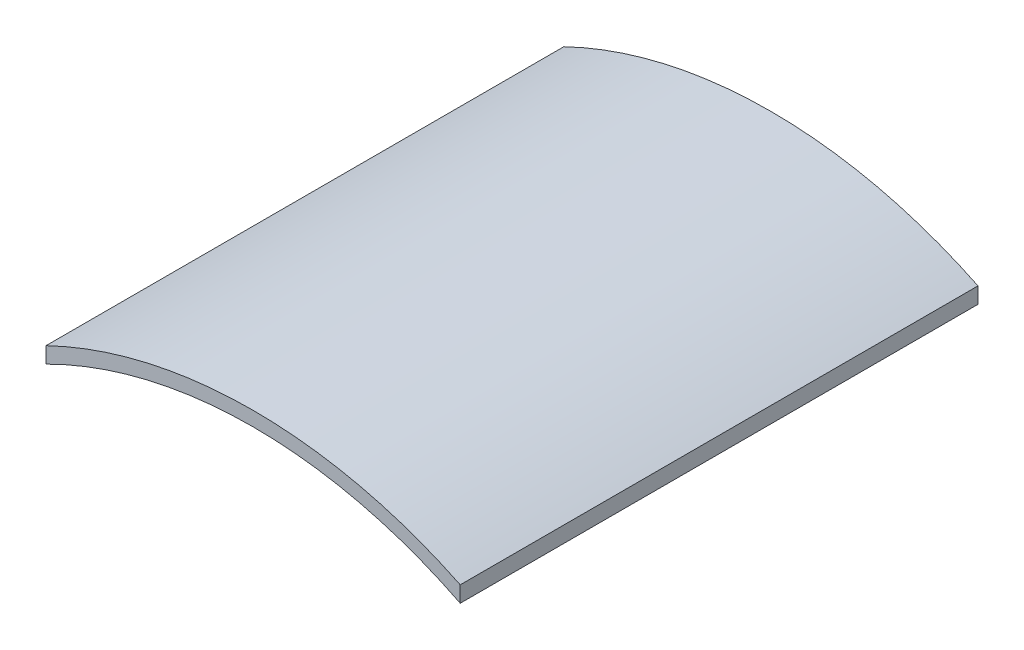
SolidWorks part; units mm, degrees
ref_plane "Front Plane" through (0, 0, 0) normal (0, 0, 1) x (1, 0, 0)
ref_plane "Top Plane" through (0, 0, 0) normal (0, 1, 0) x (1, 0, 0)
ref_plane "Right Plane" through (0, 0, 0) normal (1, 0, 0) x (0, 0, -1)
sketch "Sketch1" plane through (0, 0, 0) normal (0, 0, 1) x (1, 0, 0)
  line L4 (-24, 49.4874) -> (-24, 47.6338)
  line L5 (24, 49.4874) -> (24, 47.6338)
  arc A0 (-24, 49.4874) -> (24, 49.4874) centre (0, 0) cw
  arc A1 (-24, 47.6338) -> (24, 47.6338) centre (0, 0) cw
  point P9 (0, 53.3383)
  point P11 (-24, 48.5606)
  dimension "D1" = 1.8536
  dimension "D2" = 53.3383
  dimension "D4" = 48
extrude "Boss-Extrude1" add sketch "Sketch1" along normal blind 60
